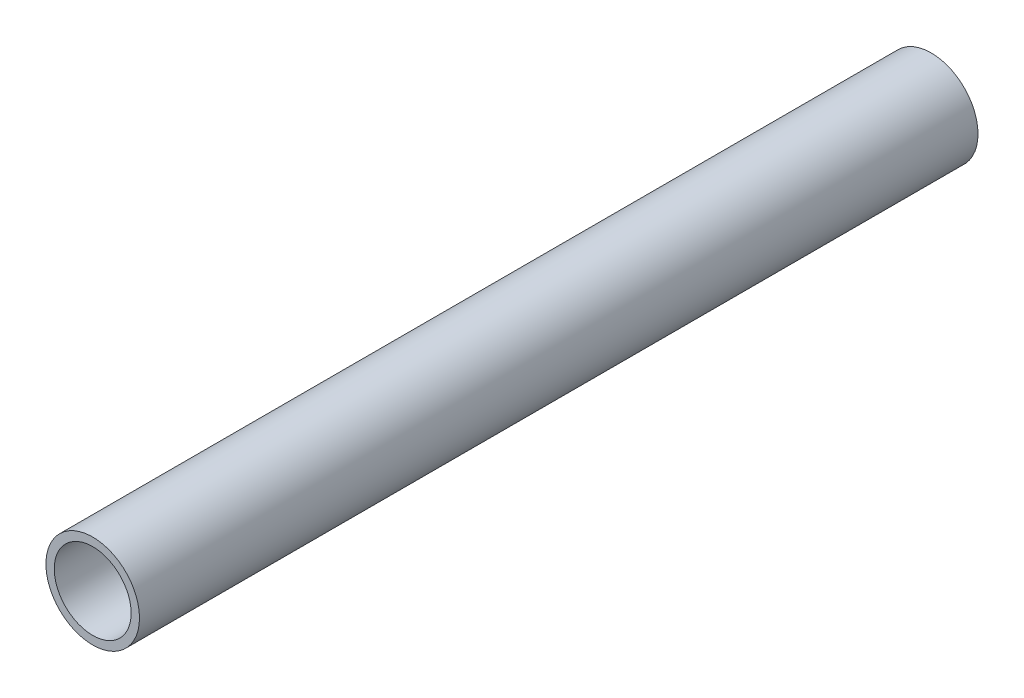
SolidWorks part; units mm, degrees
material "AISI 304"
ref_plane "Спереди" through (0, 0, 0) normal (0, 0, 1) x (1, 0, 0)
ref_plane "Сверху" through (0, 0, 0) normal (0, 1, 0) x (1, 0, 0)
ref_plane "Справа" through (0, 0, 0) normal (1, 0, 0) x (0, 0, -1)
sketch "Эскиз1" plane through (0, 0, 0) normal (0, 0, 1) x (1, 0, 0)
  circle A0 centre (0, 0) radius 16.85
  circle A1 centre (0, 0) radius 13.85
  dimension "D2" = 33.7
  dimension "D1" = 3
extrude "Бобышка-Вытянуть1" add sketch "Эскиз1" along normal mid plane 302
